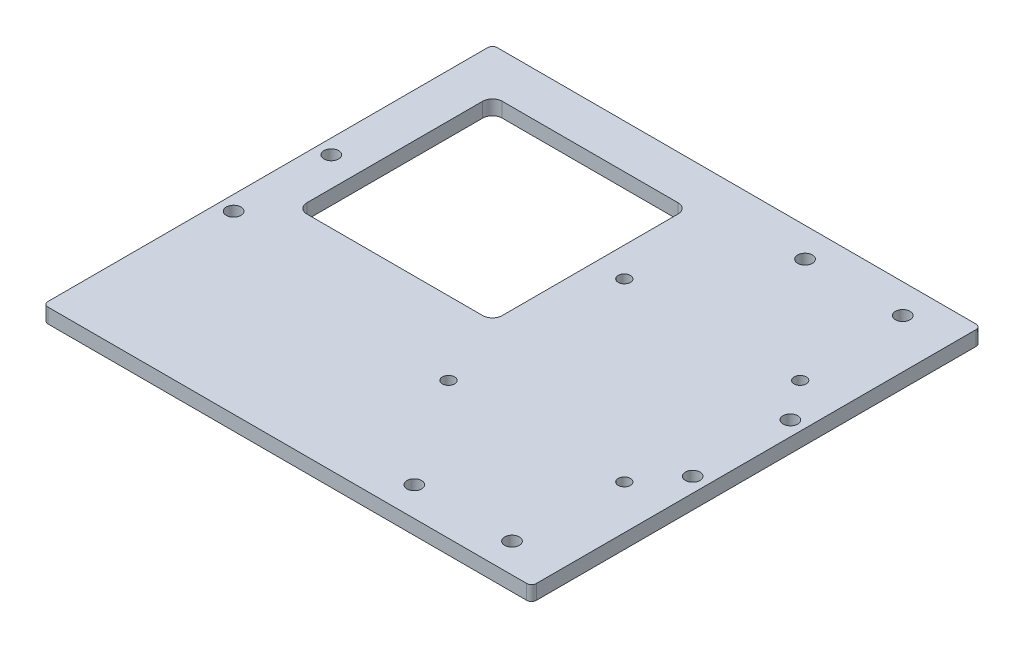
SolidWorks part; units mm, degrees
ref_plane "前视基准面" through (0, 0, 0) normal (0, 0, 1) x (1, 0, 0)
ref_plane "上视基准面" through (0, 0, 0) normal (0, 1, 0) x (1, 0, 0)
ref_plane "右视基准面" through (0, 0, 0) normal (1, 0, 0) x (0, 0, -1)
other "Configuration Table"
sketch "草图1" plane through (0, 0, 0) normal (0, 1, 0) x (1, 0, 0)
  line L5 (0, 0) -> (100, 0)
  line L6 (0, 0) -> (0, 92)
  line L7 (0, 92) -> (100, 92)
  line L8 (100, 0) -> (100, 92)
  dimension "D1" = 100
  dimension "D2" = 92
extrude "凸台-拉伸1" add sketch "草图1" along normal blind 3
sketch "草图2" plane through (0, 3, 0) normal (0, 1, 0) x (1, 0, 0)
  line L0 (97, 56) -> (97, 36) construction
  line L1 (70, 86) -> (90, 86) construction
  line L2 (70, 86) -> (70, 6) construction
  line L3 (70, 6) -> (90, 6) construction
  line L4 (90, 86) -> (90, 6) construction
  line L5 (70, 86) -> (90, 6) construction
  line L6 (70, 6) -> (90, 86) construction
  line L7 (100, 0) -> (100, 92) construction
  line L8 (80, 46) -> (100, 46) construction
  line L10 (50, 0) -> (50, 92) construction
  line L11 (0, 0) -> (100, 0) construction
  line L12 (100, 92) -> (0, 92) construction
  circle A0 centre (90, 86) radius 1.5
  circle A1 centre (70, 86) radius 1.5
  circle A2 centre (70, 6) radius 1.5
  circle A3 centre (90, 6) radius 1.5
  circle A4 centre (97, 56) radius 1.5
  circle A5 centre (97, 36) radius 1.5
  circle A6 centre (3, 36) radius 1.5
  circle A7 centre (3, 56) radius 1.5
  point P0 (80, 46)
  point P17 (97, 46)
  dimension "D3" = 3
  dimension "D4" = 3
  dimension "D1" = 80
  dimension "D2" = 20
  dimension "D5" = 10
  dimension "D6" = 20
  dimension "D7" = 3
extrude "切除-拉伸1" cut sketch "草图2" against normal through all
sketch "草图3" plane through (0, 3, 0) normal (0, 1, 0) x (1, 0, 0)
  line L1 (9, 43) -> (49, 43)
  line L2 (9, 43) -> (9, 83)
  line L3 (9, 83) -> (49, 83)
  line L4 (49, 43) -> (49, 83)
  line L5 (9, 43) -> (49, 83) construction
  line L6 (9, 83) -> (49, 43) construction
  line L10 (70, 86) -> (0, 86) construction
  line L11 (0, 92) -> (0, 0) construction
  point P0 (29, 63)
  dimension "D3" = 3
  dimension "D4" = 9
  dimension "D5" = 40
  dimension "D6" = 40
extrude "切除-拉伸2" cut sketch "草图3" against normal blind 10
fillet "圆角1" radius 2 4 edges at (49, 1.5, -83) (49, 1.5, -43) (9, 1.5, -43) (9, 1.5, -83)
fillet "圆角2" radius 1 4 edges at (100, 1.5, -92) (100, 1.5, 0) (0, 1.5, 0) (0, 1.5, -92)
sketch "草图4" plane through (0, 0, 0) normal (0, -1, 0) x (1, 0, 0)
  line L0 (73, -46) -> (100, -46) construction
  line L1 (55, -28) -> (91, -28) construction
  line L2 (55, -28) -> (55, -64) construction
  line L3 (55, -64) -> (91, -64) construction
  line L4 (91, -28) -> (91, -64) construction
  line L5 (55, -28) -> (91, -64) construction
  line L6 (55, -64) -> (91, -28) construction
  line L7 (100, -1) -> (100, -91) construction
  circle A0 centre (55, -28) radius 1.25
  circle A1 centre (91, -28) radius 1.25
  circle A2 centre (55, -64) radius 1.25
  circle A3 centre (91, -64) radius 1.25
  point P0 (73, -46)
  dimension "D2" = 2.5
  dimension "D1" = 36
  dimension "D3" = 36
  dimension "D4" = 45
extrude "切除-拉伸3" cut sketch "草图4" against normal blind 10
